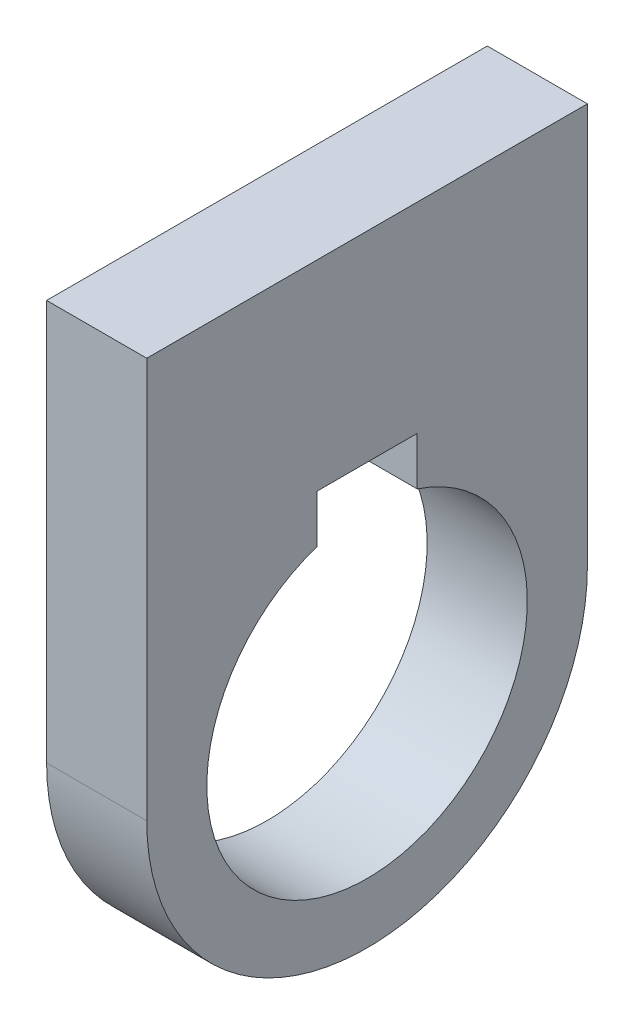
SolidWorks part; units mm, degrees
ref_plane "Front Plane" through (0, 0, 0) normal (0, 0, 1) x (1, 0, 0)
ref_plane "Top Plane" through (0, 0, 0) normal (0, 1, 0) x (1, 0, 0)
ref_plane "Right Plane" through (0, 0, 0) normal (1, 0, 0) x (0, 0, -1)
sketch "Sketch1" plane through (0, 0, 0) normal (1, 0, 0) x (0, 0, -1)
  line L0 (-16.4179, -8) -> (21.3296, -8) construction
  line L1 (-2.5, 10) -> (2.5, 10)
  line L2 (-2.5, 10) -> (-2.5, 7.5993)
  line L4 (2.5, 10) -> (2.5, 7.5993)
  line L5 (-11, 0) -> (-11, 20)
  line L6 (-11, 20) -> (11, 20)
  line L7 (11, 20) -> (11, 0)
  arc A0 (-11, 0) -> (11, 0) centre (0, 0) ccw
  arc A1 (-2.5, 7.5993) -> (2.5, 7.5993) centre (0, 0) ccw
  point P1 (0, 0)
  point P5 (0, 10)
  point P9 (0, 0)
  dimension "D1" = 22
  dimension "D3" = 16
  dimension "D2" = 18
  dimension "D4" = 5
  dimension "D5" = 20
extrude "Boss-Extrude1" add sketch "Sketch1" along normal blind 5
